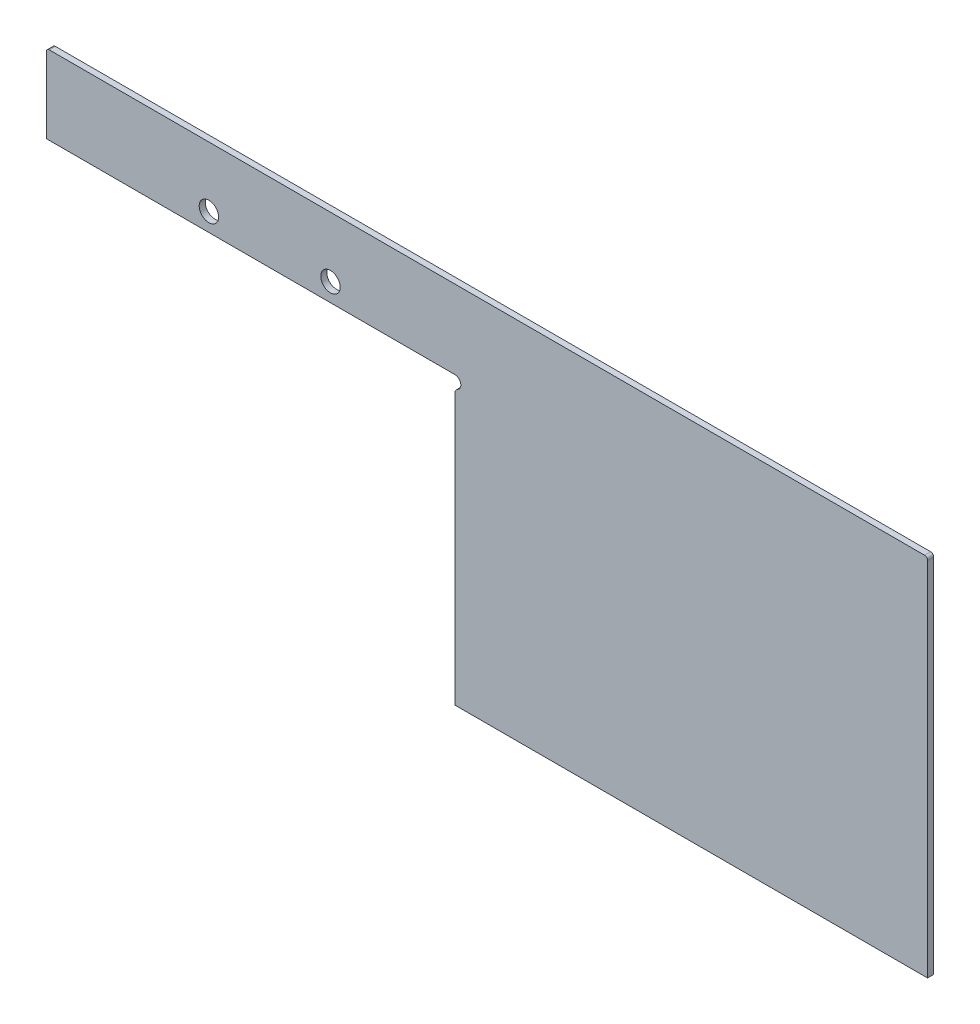
SolidWorks part; units mm, degrees
ref_plane "前视基准面" through (0, 0, 0) normal (0, 0, 1) x (1, 0, 0)
ref_plane "上视基准面" through (0, 0, 0) normal (0, 1, 0) x (1, 0, 0)
ref_plane "右视基准面" through (0, 0, 0) normal (1, 0, 0) x (0, 0, -1)
sketch "草图1" plane through (0, 0, 0) normal (0, 0, 1) x (1, 0, 0)
  line L0 (0, 0) -> (0, 12.9)
  line L1 (0, 12.9) -> (146, 12.9)
  line L2 (146, 12.9) -> (146, -47.1)
  line L3 (146, -47.1) -> (67.7, -47.1)
  line L4 (67.7, -47.1) -> (67.7, 0)
  line L5 (67.7, 0) -> (0, 0)
  line L6 (27.25, 3) -> (47.25, 3) construction
  circle A0 centre (47.25, 3) radius 1.6
  circle A1 centre (27.25, 3) radius 1.6
  dimension "D6" = 3.2
  dimension "D1" = 67.7
  dimension "D2" = 12.9
  dimension "D3" = 146
  dimension "D4" = 60
  dimension "D5" = 20
  dimension "D7" = 3
  dimension "D8" = 27.25
extrude "凸台-拉伸1" add sketch "草图1" along normal blind 1
sketch "草图2" plane through (0, 0, 1) normal (0, 0, 1) x (1, 0, 0)
  line L0 (67.7, 0) -> (67.7, -47.1) construction
  circle A0 centre (67.7, -1) radius 1
  dimension "D1" = 2
extrude "切除-拉伸1" cut sketch "草图2" against normal blind 10
fillet "圆角1" radius 1 1 edges at (67.7, -2, 0.5)
sketch "草图3" plane through (0, 0, 1) normal (0, 0, 1) x (1, 0, 0)
  line L0 (0, 0) -> (67.7, 0) construction
  line L1 (0, 12.9) -> (0.5, 12.9)
  line L2 (0, 12.9) -> (0, 0)
  line L3 (0, 0) -> (0.5, 0)
  line L4 (0.5, 12.9) -> (0.5, 0)
  line L5 (67.7, -47.1) -> (146, -47.1) construction
  line L6 (146, 12.9) -> (145.5, 12.9)
  line L7 (146, 12.9) -> (146, -47.1)
  line L8 (146, -47.1) -> (145.5, -47.1)
  line L9 (145.5, 12.9) -> (145.5, -47.1)
  dimension "D1" = 0.5
extrude "切除-拉伸2" cut sketch "草图3" against normal through all
fillet "圆角2" radius 0.5 2 edges at (0.5, 12.9, 0.5) (145.5, 12.9, 0.5)
